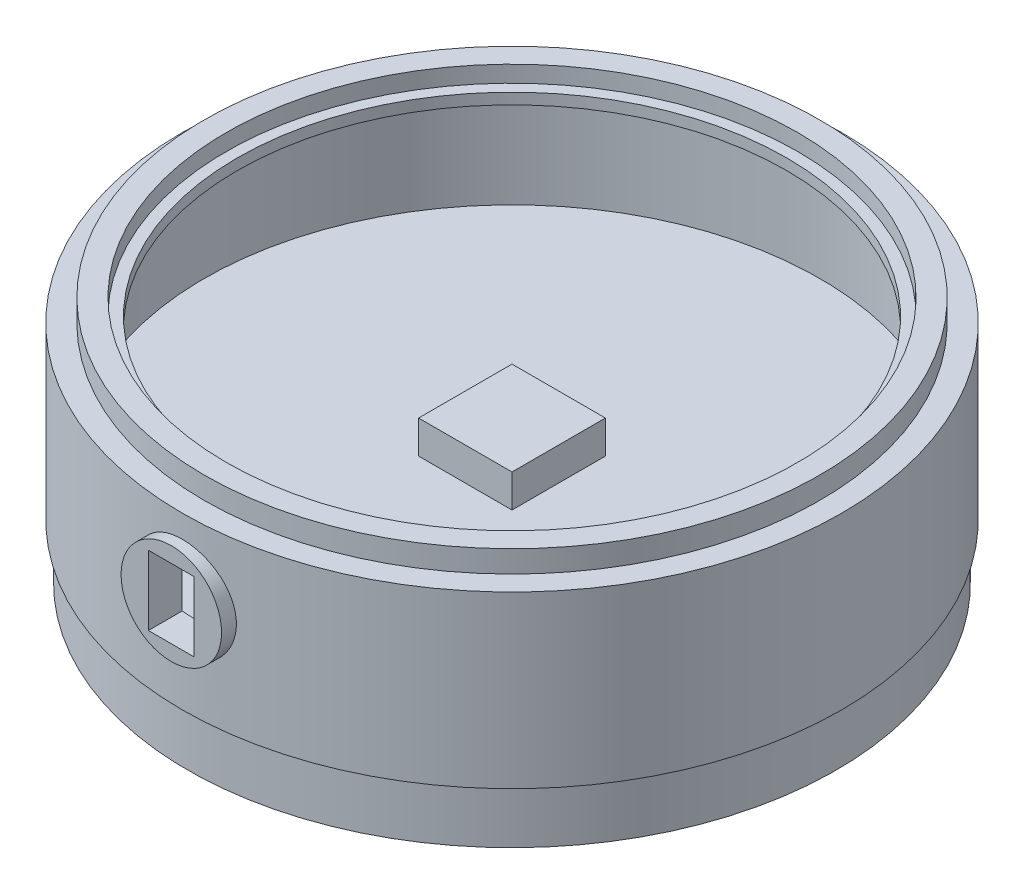
SolidWorks part; units mm, degrees
ref_plane "前视基准面" through (0, 0, 0) normal (0, 0, 1) x (1, 0, 0)
ref_plane "上视基准面" through (0, 0, 0) normal (0, 1, 0) x (1, 0, 0)
ref_plane "右视基准面" through (0, 0, 0) normal (1, 0, 0) x (0, 0, -1)
sketch "草图1" plane through (0, 0, 0) normal (0, 1, 0) x (1, 0, 0)
  circle A0 centre (0, 0) radius 30
extrude "凸台-拉伸1" add sketch "草图1" along normal blind 1
sketch "草图10" plane through (0, 1, 0) normal (0, 1, 0) x (1, 0, 0)
  circle A0 centre (0, 0) radius 30
  circle A1 centre (0, 0) radius 28
extrude "凸台-拉伸4" add sketch "草图10" along normal blind 10
sketch "草图6" plane through (0, 1, 0) normal (0, 1, 0) x (1, 0, 0)
  line L5 (-3.7649, 26.9158) -> (3.2351, 26.9158)
  line L6 (-3.7649, 26.9158) -> (-3.7649, 23.9158)
  line L8 (-3.7649, 23.9158) -> (3.2351, 23.9158)
  line L17 (3.2351, 23.9158) -> (3.2351, 26.9158)
  circle A1 centre (0, -23.2424) radius 4
extrude "切除-拉伸2" [suppressed] cut sketch "草图6" against normal through all
sketch "草图11" plane through (0, 1, 0) normal (0, 1, 0) x (1, 0, 0)
  line L1 (-4.25, -4.25) -> (4.25, -4.25)
  line L2 (-4.25, -4.25) -> (-4.25, 4.25)
  line L3 (-4.25, 4.25) -> (4.25, 4.25)
  line L4 (4.25, -4.25) -> (4.25, 4.25)
  line L5 (-4.25, -4.25) -> (4.25, 4.25) construction
  line L6 (-4.25, 4.25) -> (4.25, -4.25) construction
  point P0 (0, 0)
extrude "凸台-拉伸5" add sketch "草图11" along normal blind 3
sketch "草图16" plane through (0, 11, 0) normal (0, 1, 0) x (1, 0, 0)
  circle A0 centre (0, 0) radius 28
  circle A1 centre (0, 0) radius 29
extrude "切除-拉伸3" [suppressed] cut sketch "草图16" against normal blind 2
sketch "草图17" plane through (0, 0, 0) normal (0, 0, 1) x (1, 0, 0)
  circle A0 centre (0, 4.8766) radius 4.5713
extrude "凸台-拉伸6" add sketch "草图17" along normal blind 2 from offset 29
sketch "草图18" plane through (0, 0, 31) normal (0, 0, 1) x (1, 0, 0)
  line L9 (-2.0871, 1.7133) -> (2.0871, 1.7133)
  line L10 (-2.0871, 1.7133) -> (-2.0871, 8.0399)
  line L11 (-2.0871, 8.0399) -> (2.0871, 8.0399)
  line L12 (2.0871, 1.7133) -> (2.0871, 8.0399)
  line L13 (-2.0871, 1.7133) -> (2.0871, 8.0399) construction
  line L14 (-2.0871, 8.0399) -> (2.0871, 1.7133) construction
  point P0 (0, 4.8766)
extrude "切除-拉伸5" cut sketch "草图18" against normal blind 10
sketch "草图19" plane through (0, 11, 0) normal (0, 1, 0) x (1, 0, 0)
  circle A4 centre (0, 0) radius 30
  circle A5 centre (0, 0) radius 25
extrude "凸台-拉伸7" add sketch "草图19" along normal blind 1
sketch "草图23" plane through (0, 12, 0) normal (0, 1, 0) x (1, 0, 0)
  circle A0 centre (0, 0) radius 26
  circle A1 centre (0, 0) radius 30
extrude "凸台-拉伸8" add sketch "草图23" along normal blind 1.5
sketch "草图24" plane through (0, 13.5, 0) normal (0, 1, 0) x (1, 0, 0)
  circle A0 centre (0, 0) radius 28
  circle A1 centre (0, 0) radius 32
extrude "切除-拉伸6" cut sketch "草图24" against normal blind 2
sketch "草图25" plane through (0, 0, 0) normal (0, -1, 0) x (1, 0, 0)
  circle A0 centre (0, 0) radius 30
extrude "凸台-拉伸9" add sketch "草图25" along normal blind 4
sketch "草图26" plane through (0, -4, 0) normal (0, -1, 0) x (-1, 0, 0)
  circle A0 centre (-10.2596, 17.0345) radius 1.5
  circle A1 centre (10.7404, 17.0345) radius 1.5
  circle A2 centre (10.7404, -16.9655) radius 1.5
  circle A3 centre (-10.2596, -16.9655) radius 1.5
extrude "切除-拉伸7" cut sketch "草图26" against normal blind 4
sketch "草图27" plane through (0, -4, 0) normal (0, -1, 0) x (1, 0, 0)
  circle A0 centre (0, 0) radius 29.5
  circle A1 centre (-10.7404, 16.9655) radius 1.5
  circle A2 centre (-10.7404, -17.0345) radius 1.5
  circle A3 centre (10.2596, -17.0345) radius 1.5
  circle A4 centre (10.2596, 16.9655) radius 1.5
extrude "凸台-拉伸10" add sketch "草图27" along normal blind 5
